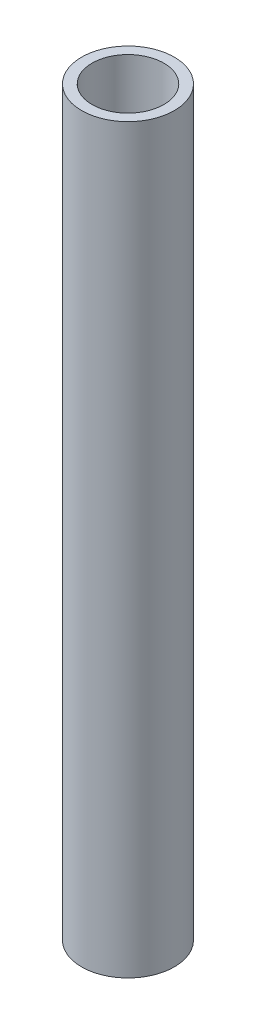
SolidWorks part; units mm, degrees
ref_plane "Front Plane" through (0, 0, 0) normal (0, 0, 1) x (1, 0, 0)
ref_plane "Top Plane" through (0, 0, 0) normal (0, 1, 0) x (1, 0, 0)
ref_plane "Right Plane" through (0, 0, 0) normal (1, 0, 0) x (0, 0, -1)
sketch "Sketch1" plane through (0, 0, 0) normal (0, 1, 0) x (1, 0, 0)
  circle A0 centre (0, 0) radius 6.35
  circle A1 centre (0, 0) radius 4.9213
  dimension "D1" = 12.7
  dimension "D2" = 9.8425
extrude "Boss-Extrude1" add sketch "Sketch1" along normal blind 101.6
